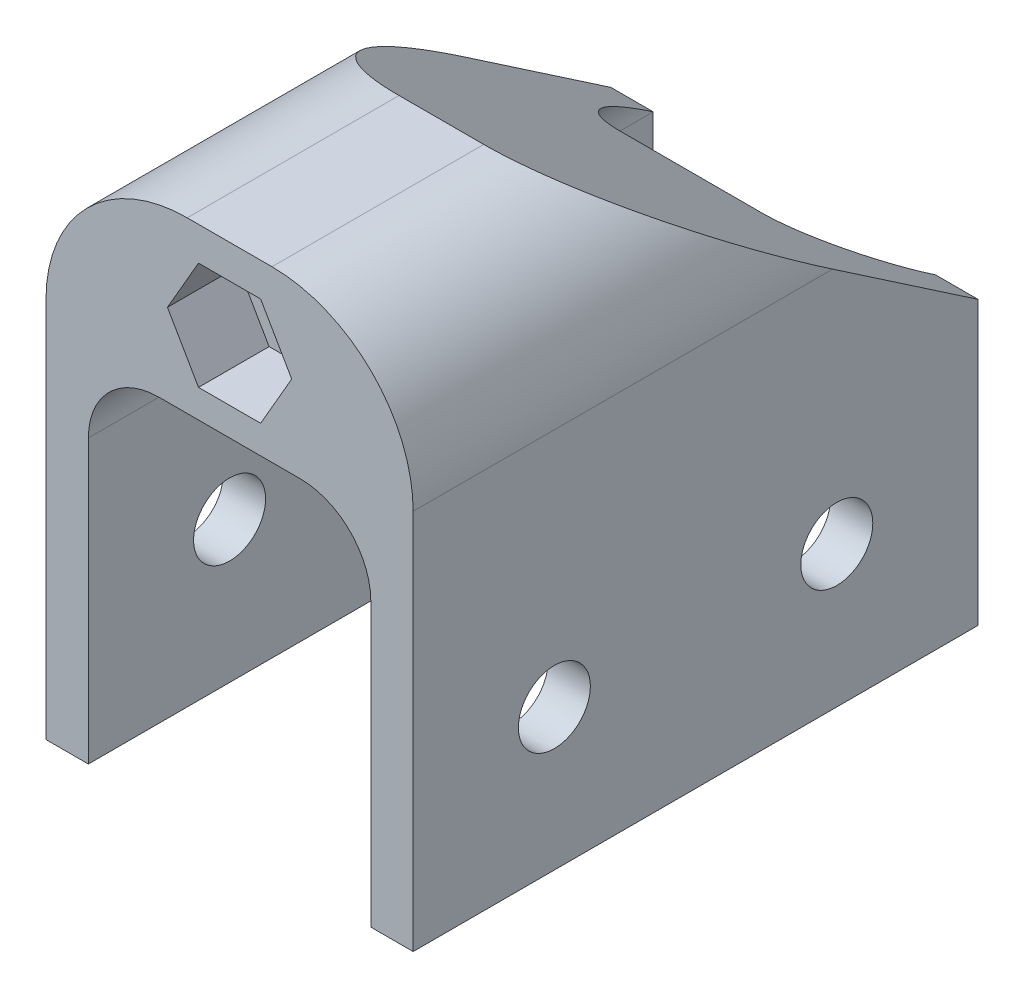
SolidWorks part; units mm, degrees
ref_plane "Спереди" through (0, 0, 0) normal (0, 0, 1) x (1, 0, 0)
ref_plane "Сверху" through (0, 0, 0) normal (0, 1, 0) x (1, 0, 0)
ref_plane "Справа" through (0, 0, 0) normal (1, 0, 0) x (0, 0, -1)
sketch "Эскиз1" plane through (0, 0, 0) normal (0, 0, 1) x (1, 0, 0)
  line L0 (0, 0) -> (0, 20)
  line L1 (5, 25) -> (15, 25)
  line L2 (20, 20) -> (20, 0)
  line L3 (20, 0) -> (23, 0)
  line L4 (23, 0) -> (23, 27)
  line L6 (-3, 27) -> (-3, 0)
  line L7 (-3, 0) -> (0, 0)
  line L8 (7, 37) -> (13, 37)
  arc A1 (15, 25) -> (20, 20) centre (15, 20) cw
  arc A2 (0, 20) -> (5, 25) centre (5, 20) cw
  arc A3 (23, 27) -> (13, 37) centre (13, 27) ccw
  arc A4 (7, 37) -> (-3, 27) centre (7, 27) ccw
  point P20 (20, 25)
  point P23 (0, 25)
  dimension "D7" = 5
  dimension "D8" = 10
  dimension "D1" = 25
  dimension "D2" = 20
  dimension "D3" = 3
  dimension "D4" = 3
extrude "Бобышка-Вытянуть1" add sketch "Эскиз1" along normal blind 40
sketch "Эскиз2" plane through (23, 0, 0) normal (1, 0, 0) x (0, 0, -1)
  line L0 (0, 20) -> (-25, 37)
  line L1 (0, 0) -> (0, 27) construction
  line L2 (-40, 37) -> (0, 37) construction
  line L3 (-25, 37) -> (0, 37)
  line L4 (0, 37) -> (0, 20)
  line L5 (-40, 0) -> (0, 0) construction
  line L6 (-40, 37) -> (-40, 27) construction
  dimension "D1" = 20
  dimension "D2" = 15
extrude "Вырез-Вытянуть1" cut sketch "Эскиз2" against normal through all
sketch "Эскиз3" plane through (23, 0, 0) normal (1, 0, 0) x (0, 0, -1)
  line L0 (-42.5274, 10) -> (4.9065, 10) construction
  line L1 (-40, 0) -> (0, 0) construction
  line L2 (-40, 0) -> (-40, 27) construction
  line L3 (0, 0) -> (0, 20) construction
  circle A0 centre (-30, 10) radius 2.55
  circle A1 centre (-10, 10) radius 2.55
  dimension "D2" = 5.1
  dimension "D3" = 5.1
  dimension "D5" = 10
  dimension "D1" = 10
  dimension "D4" = 10
extrude "Вырез-Вытянуть2" cut sketch "Эскиз3" against normal through all
sketch "Эскиз4" plane through (0, 0, 40) normal (0, 0, 1) x (1, 0, 0)
  line L0 (5, 25) -> (15, 25) construction
  line L7 (5.6, 30.8105) -> (7.8, 27)
  line L8 (7.8, 27) -> (12.2, 27)
  line L9 (12.2, 27) -> (14.4, 30.8105)
  line L10 (14.4, 30.8105) -> (12.2, 34.621)
  line L11 (12.2, 34.621) -> (7.8, 34.621)
  line L12 (7.8, 34.621) -> (5.6, 30.8105)
  circle A0 centre (10, 30.8105) radius 4.4 construction
  point P10 (10, 27)
  dimension "D1" = 2
extrude "Вырез-Вытянуть3" cut sketch "Эскиз4" against normal blind 5
ref_plane "Плоскость1" through (0, 0, 50) normal (0, 0, 1) x (1, 0, 0)
sketch "Эскиз6" plane through (0, 0, 35) normal (0, 0, 1) x (1, 0, 0)
  circle A0 centre (10, 30.8105) radius 2.55
  dimension "D1" = 5.1
extrude "Вырез-Вытянуть4" cut sketch "Эскиз6" against normal blind 1
